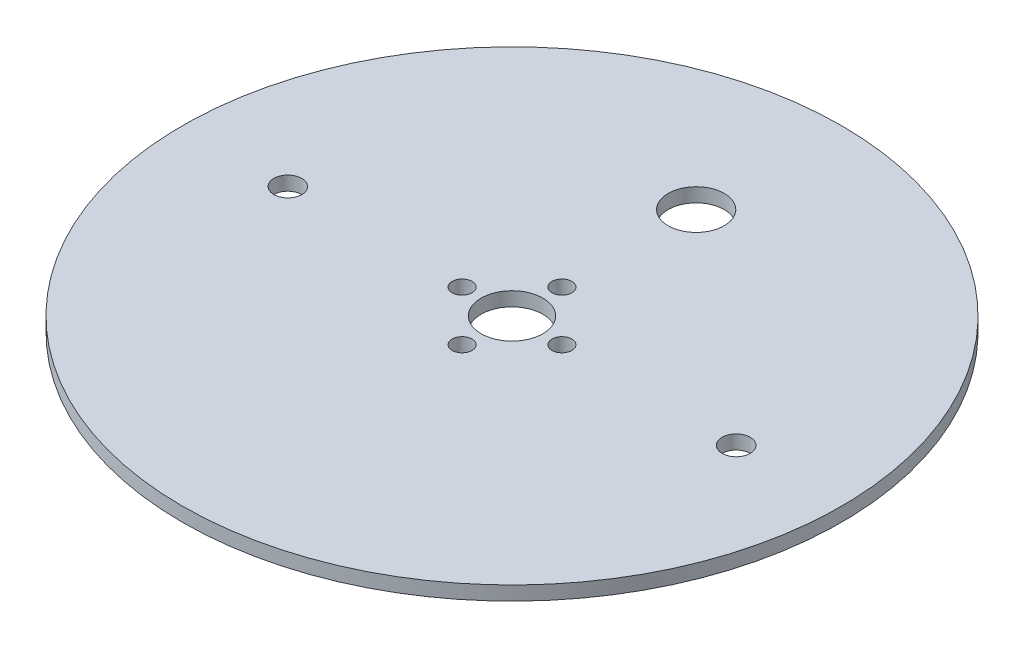
SolidWorks part; units mm, degrees
ref_plane "Front Plane" through (0, 0, 0) normal (0, 0, 1) x (1, 0, 0)
ref_plane "Top Plane" through (0, 0, 0) normal (0, 1, 0) x (1, 0, 0)
ref_plane "Right Plane" through (0, 0, 0) normal (1, 0, 0) x (0, 0, -1)
sketch "Sketch1" plane through (0, 0, 0) normal (0, 1, 0) x (1, 0, 0)
  circle A0 centre (0, 0) radius 74.676
  dimension "D1" = 149.352
extrude "Boss-Extrude1" add sketch "Sketch1" along normal blind 3.175
sketch "Sketch2" plane through (0, 3.175, 0) normal (0, 1, 0) x (1, 0, 0)
  circle A0 centre (0, 0) radius 7
  dimension "D1" = 14
extrude "Cut-Extrude1" cut sketch "Sketch2" against normal through all
sketch "Sketch3" plane through (0, 3.175, 0) normal (0, 1, 0) x (1, 0, 0)
  circle A0 centre (11.314, 0) radius 2.25
  circle A1 centre (0, 0) radius 7 construction
  circle A2 centre (0, -11.314) radius 2.25
  circle A3 centre (-11.314, 0) radius 2.25
  circle A4 centre (0, 11.314) radius 2.25
  point P13 (0, 0)
  dimension "D1" = 4.5
  dimension "D2" = 11.314
  dimension "D3" = 4
extrude "Cut-Extrude2" cut sketch "Sketch3" against normal through all
sketch "Sketch4" plane through (0, 3.175, 0) normal (0, 1, 0) x (1, 0, 0)
  circle A0 centre (50.8, 0) radius 3.175 construction
  circle A1 centre (-50.8, 0) radius 3.175 construction
  circle A2 centre (50.8, 0) radius 3.175
  circle A3 centre (-50.8, 0) radius 3.175
extrude "Cut-Extrude3" cut sketch "Sketch4" against normal through all
sketch "Sketch6" plane through (0, 3.175, 0) normal (0, 1, 0) x (1, 0, 0)
  circle A0 centre (0, 41.7338) radius 6.35 construction
  circle A3 centre (0, 41.7338) radius 6.35
extrude "Cut-Extrude5" cut sketch "Sketch6" against normal up to next
